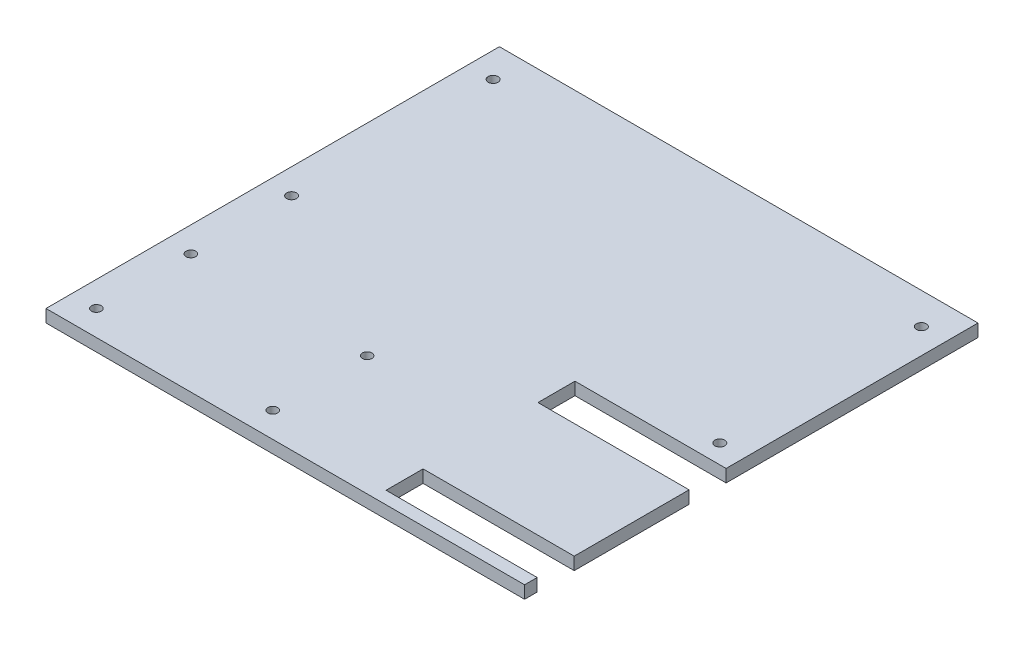
SolidWorks part; units mm, degrees
ref_plane "Front Plane" through (0, 0, 0) normal (0, 0, 1) x (1, 0, 0)
ref_plane "Top Plane" through (0, 0, 0) normal (0, 1, 0) x (1, 0, 0)
ref_plane "Right Plane" through (0, 0, 0) normal (1, 0, 0) x (0, 0, -1)
sketch "Sketch1" plane through (0, 0, 0) normal (0, 1, 0) x (1, 0, 0)
  line L0 (-114.3, 107.95) -> (114.3, 107.95) construction
  line L1 (-120.65, 114.3) -> (120.65, 114.3)
  line L2 (-120.65, 114.3) -> (-120.65, -114.3)
  line L3 (-120.65, -114.3) -> (120.65, -114.3)
  line L4 (120.65, 114.3) -> (120.65, -114.3)
  line L5 (-120.65, 114.3) -> (120.65, -114.3) construction
  line L6 (-120.65, -114.3) -> (120.65, 114.3) construction
  line L7 (114.3, 107.95) -> (114.3, -107.95) construction
  line L8 (-114.3, -107.95) -> (114.3, -107.95) construction
  line L9 (-114.3, 107.95) -> (-114.3, -107.95) construction
  line L10 (44.45, -31.369) -> (120.65, -31.369)
  line L15 (44.45, -89.281) -> (120.65, -89.281)
  line L16 (44.45, -89.281) -> (44.45, -107.95)
  line L17 (44.45, -12.7) -> (120.65, -12.7)
  line L18 (44.45, -12.7) -> (44.45, -31.369)
  line L19 (44.45, -107.95) -> (120.65, -107.95)
  line L20 (120.65, -12.7) -> (120.65, -31.369)
  line L23 (120.65, -89.281) -> (120.65, -107.95)
  circle A0 centre (-107.95, -101.6) radius 2.4257
  circle A1 centre (-107.95, -53.975) radius 2.4257
  circle A2 centre (-19.05, -53.975) radius 2.4257
  circle A3 centre (-19.05, -101.6) radius 2.4257
  circle A4 centre (-107.95, 98.425) radius 2.5019
  circle A5 centre (-107.95, -3.175) radius 2.5019
  circle A6 centre (107.95, 98.425) radius 2.5019
  circle A7 centre (107.95, -3.175) radius 2.5019
  point P0 (0, 0)
  point P31 (0, 0)
  point P32 (0, 0)
  dimension "D4" = 4.8514
  dimension "D7" = 47.625
  dimension "D8" = 88.9
  dimension "D13" = 5.0038
  dimension "D14" = 101.6
  dimension "D15" = 50.8
  dimension "D16" = 215.9
  dimension "D1" = 241.3
  dimension "D2" = 228.6
  dimension "D5" = 6.35
  dimension "D6" = 6.35
  dimension "D9" = 18.669
  dimension "D17" = 95.25
  dimension "D18" = 76.2
  dimension "D3" = 6.35
extrude "Boss-Extrude1" add sketch "Sketch1" along normal blind 6.35 contours L19 L16 L15 L4 L10 L18 L17 L1 L2 L3 A7 A6 A5 A4 A3 A2 A1 A0
